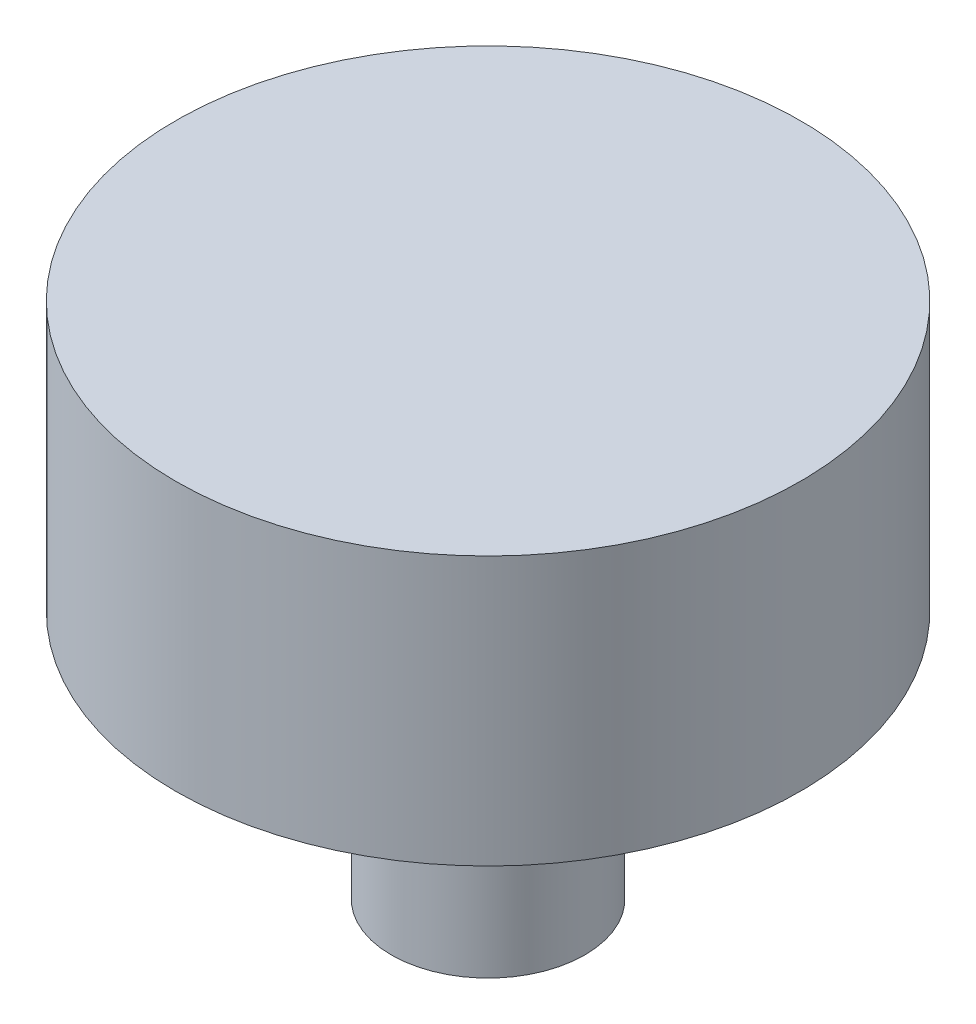
SolidWorks part; units mm, degrees
ref_plane "Front Plane" through (0, 0, 0) normal (0, 0, 1) x (1, 0, 0)
ref_plane "Top Plane" through (0, 0, 0) normal (0, 1, 0) x (1, 0, 0)
ref_plane "Right Plane" through (0, 0, 0) normal (1, 0, 0) x (0, 0, -1)
sketch "Sketch1" plane through (0, 0, 0) normal (0, 1, 0) x (1, 0, 0)
  circle A0 centre (0, 0) radius 20.701
  dimension "D1" = 41.402
extrude "Boss-Extrude1" add sketch "Sketch1" along normal blind 17.7927
sketch "Sketch3" plane through (0, 0, 0) normal (0, -1, 0) x (1, 0, 0)
  circle A0 centre (0, 0) radius 6.4135
  dimension "D1" = 12.827
extrude "Boss-Extrude2" add sketch "Sketch3" along normal blind 16.5354
